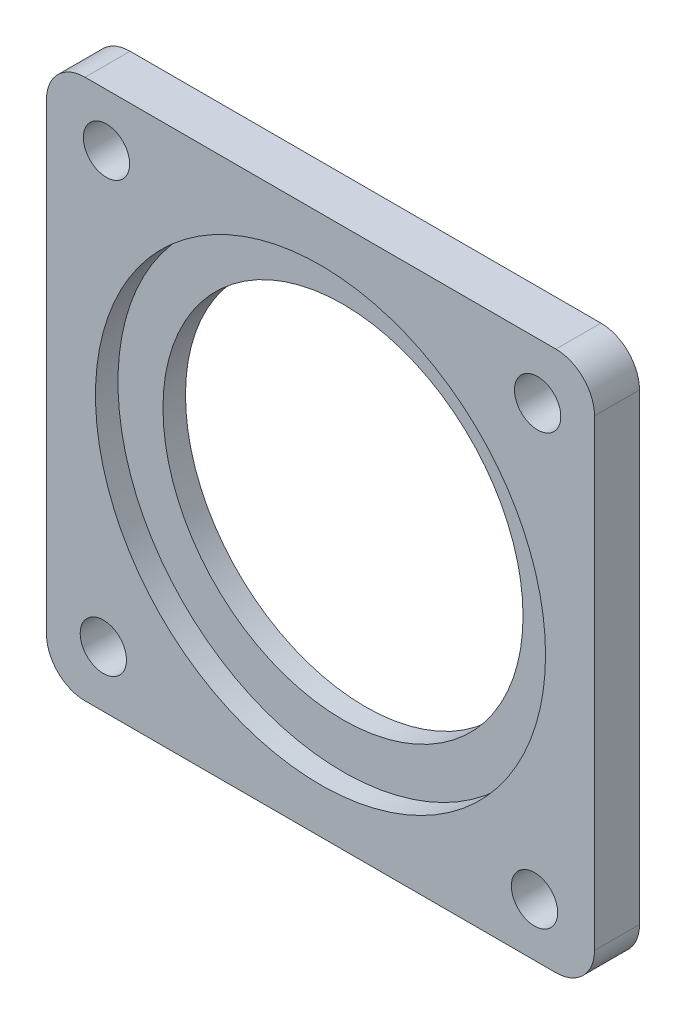
SolidWorks part; units mm, degrees
ref_plane "Płaszczyzna przednia" through (0, 0, 0) normal (0, 0, 1) x (1, 0, 0)
ref_plane "Płaszczyzna górna" through (0, 0, 0) normal (0, 1, 0) x (1, 0, 0)
ref_plane "Płaszczyzna prawa" through (0, 0, 0) normal (1, 0, 0) x (0, 0, -1)
sketch "Sketch1" plane through (0, 0, 0) normal (0, 0, 1) x (1, 0, 0)
  line L1 (21.3073, -21) -> (-21.3073, -21)
  line L2 (21.3073, -21) -> (21.3073, 21)
  line L3 (21.3073, 21) -> (-21.3073, 21)
  line L4 (-21.3073, -21) -> (-21.3073, 21)
  line L5 (21.3073, -21) -> (-21.3073, 21) construction
  line L6 (21.3073, 21) -> (-21.3073, -21) construction
  circle A0 centre (0, 0) radius 21 construction
  circle A1 centre (0, 0) radius 14
  dimension "D1" = 42
  dimension "D2" = 28
extrude "Boss-Extrude1" add sketch "Sketch1" along normal blind 3.5
sketch "Sketch2" plane through (0, 0, 3.5) normal (0, 0, 1) x (1, 0, 0)
  circle A0 centre (0, 0) radius 17.5
  dimension "D2" = 35
extrude "Cut-Extrude1" cut sketch "Sketch2" against normal blind 1.75
hole_wizard "M3 Clearance Hole1" positions "Sketch3" profile "Sketch4" hole size "M3" standard "DIN" end condition through all
sketch "Sketch3" plane through (0, 0, 0) normal (0, 0, -1) x (-1, 0, 0)
  line L0 (-21.3073, 21) -> (-12.4639, 12.2842) construction
  circle A0 centre (0, 0) radius 17.5 construction
  circle A1 centre (0, 0) radius 17.5
  point P9 (-16.8856, 16.6421)
  point P17 (16.6421, 16.8856)
  point P18 (16.8856, -16.6421)
  point P19 (-16.6421, -16.8856)
  dimension "D1" = 4
sketch "Sketch4" plane through (16.6421, -16.8856, 0) normal (1, 0, 0) x (0, 1, 0)
  line L0 (0, 0) -> (0, 3.5)
  line L1 (0, 3.5) -> (1.8, 3.5)
  line L2 (1.8, 3.5) -> (1.8, 0)
  line L5 (1.8, 0) -> (0, 0)
  line L11 (0, -6.35) -> (0, 107.95) construction
  dimension "Thru Hole Dia." = 3.6
  dimension "Thru Hole Depth" = 3.5
fillet "Fillet1" radius 3 4 edges at (-21.3073, 21, 1.75) (-21.3073, -21, 1.75) (21.3073, -21, 1.75) (21.3073, 21, 1.75)
